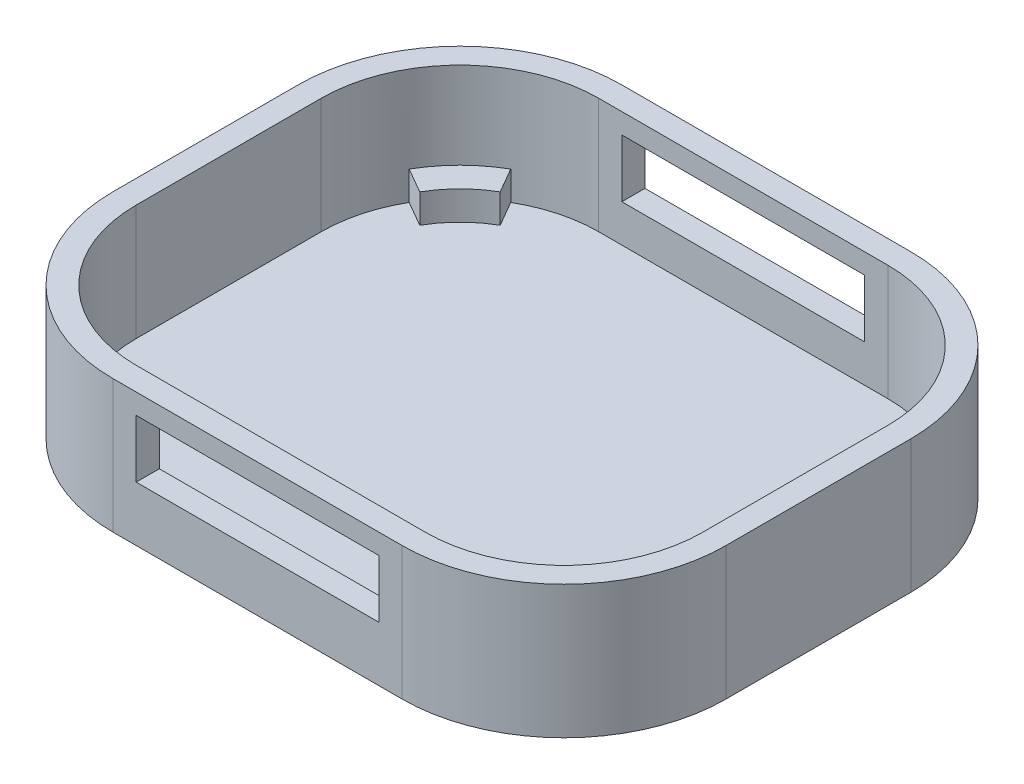
SolidWorks part; units mm, degrees
ref_plane "Front Plane" through (0, 0, 0) normal (0, 0, 1) x (1, 0, 0)
ref_plane "Top Plane" through (0, 0, 0) normal (0, 1, 0) x (1, 0, 0)
ref_plane "Right Plane" through (0, 0, 0) normal (1, 0, 0) x (0, 0, -1)
sketch "Sketch1" plane through (0, 0, 0) normal (0, 1, 0) x (1, 0, 0)
  line L0 (12.5, 22) -> (-12.5, 22) construction
  line L1 (12.5, -20) -> (-12.5, -20)
  line L2 (24.5, -8) -> (24.5, 8)
  line L3 (12.5, 20) -> (-12.5, 20)
  line L4 (-24.5, -8) -> (-24.5, 8)
  line L5 (24.5, -20) -> (-24.5, 20) construction
  line L6 (24.5, 20) -> (-24.5, -20) construction
  line L7 (26.5, -8) -> (26.5, 8) construction
  line L8 (12.5, -22) -> (-12.5, -22) construction
  line L9 (-26.5, -8) -> (-26.5, 8) construction
  line L10 (-26.5, 8) -> (-26.5, -8)
  line L11 (-12.5, -22) -> (12.5, -22)
  line L12 (26.5, -8) -> (26.5, 8)
  line L13 (12.5, 22) -> (-12.5, 22)
  arc A0 (12.5, 20) -> (24.5, 8) centre (12.5, 8) cw
  arc A1 (24.5, -8) -> (12.5, -20) centre (12.5, -8) cw
  arc A2 (-12.5, -20) -> (-24.5, -8) centre (-12.5, -8) cw
  arc A3 (-24.5, 8) -> (-12.5, 20) centre (-12.5, 8) cw
  arc A4 (-26.5, 8) -> (-12.5, 22) centre (-12.5, 8) cw construction
  arc A5 (12.5, 22) -> (26.5, 8) centre (12.5, 8) cw construction
  arc A6 (26.5, -8) -> (12.5, -22) centre (12.5, -8) cw construction
  arc A7 (-12.5, -22) -> (-26.5, -8) centre (-12.5, -8) cw construction
  arc A8 (-12.5, 22) -> (-26.5, 8) centre (-12.5, 8) ccw
  arc A9 (-26.5, -8) -> (-12.5, -22) centre (-12.5, -8) ccw
  arc A10 (12.5, -22) -> (26.5, -8) centre (12.5, -8) ccw
  arc A11 (26.5, 8) -> (12.5, 22) centre (12.5, 8) ccw
  point P0 (0, 0)
  point P33 (26.5, 0)
  point P43 (-26.5, 0)
  point P44 (0, 22)
  dimension "D3" = 12
  dimension "D1" = 53
  dimension "D2" = 44
  dimension "D5" = 16
  dimension "D4" = 2
extrude "Boss-Extrude1" add sketch "Sketch1" along normal mid plane 11.5
sketch "Sketch2" plane through (0, 0, -20) normal (0, 0, 1) x (1, 0, 0)
  line L0 (-26.5, 0) -> (26.5, 0) construction
  line L1 (-10.5, 4) -> (10.5, 4)
  line L2 (-10.5, 4) -> (-10.5, -1)
  line L3 (-10.5, -1) -> (10.5, -1)
  line L4 (10.5, 4) -> (10.5, -1)
  line L5 (-10.5, 4) -> (10.5, -1) construction
  line L6 (-10.5, -1) -> (10.5, 4) construction
  line L9 (-26.5, 5.75) -> (-26.5, -5.75) construction
  line L10 (26.5, 5.75) -> (26.5, -5.75) construction
  line L11 (0, 5.75) -> (0, -5.75) construction
  line L12 (-12.5, 5.75) -> (12.5, 5.75) construction
  line L13 (-12.5, -5.75) -> (12.5, -5.75) construction
  point P0 (0, 1.5)
  dimension "D1" = 21
  dimension "D2" = 5
  dimension "D3" = 1.75
extrude "Cut-Extrude1" cut sketch "Sketch2" against normal through all both and the other way through all
sketch "Sketch3" plane through (0, -5.75, 0) normal (0, -1, 0) x (1, 0, 0)
  line L4 (-12.5, -22) -> (12.5, -22)
  line L5 (26.5, -8) -> (26.5, 8)
  line L12 (12.5, 22) -> (-12.5, 22)
  line L13 (-26.5, 8) -> (-26.5, -8)
  line L14 (-12.5, -22) -> (12.5, -22)
  line L15 (26.5, -8) -> (26.5, 8)
  line L16 (12.5, 22) -> (-12.5, 22)
  line L17 (-26.5, 8) -> (-26.5, -8)
  arc A12 (-26.5, -8) -> (-12.5, -22) centre (-12.5, -8) ccw
  arc A13 (12.5, -22) -> (26.5, -8) centre (12.5, -8) ccw
  arc A14 (26.5, 8) -> (12.5, 22) centre (12.5, 8) ccw
  arc A15 (-12.5, 22) -> (-26.5, 8) centre (-12.5, 8) ccw
  arc A16 (-26.5, -8) -> (-12.5, -22) centre (-12.5, -8) ccw
  arc A17 (12.5, -22) -> (26.5, -8) centre (12.5, -8) ccw
  arc A18 (26.5, 8) -> (12.5, 22) centre (12.5, 8) ccw
  arc A19 (-12.5, 22) -> (-26.5, 8) centre (-12.5, 8) ccw
  dimension "D1" = 0
extrude "Boss-Extrude2" add sketch "Sketch3" against normal blind 1.5
sketch "Sketch4" plane through (0, 0, -22) normal (0, 0, -1) x (-1, 0, 0)
  line L5 (-10.5, -5) -> (10.5, -5)
  line L6 (-10.5, -5) -> (-10.5, -10)
  line L7 (-10.5, -10) -> (10.5, -10)
  line L9 (10.5, -5) -> (10.5, -10)
  line L10 (-10.5, -5) -> (10.5, -10) construction
  line L11 (-10.5, -10) -> (10.5, -5) construction
  point P0 (0, -7.5)
  dimension "D1" = 5
  dimension "D2" = 21
  dimension "D3" = 7.5
extrude "Cut-Extrude2" [suppressed] cut sketch "Sketch4" against normal blind 2
sketch "Sketch5" plane through (0, -4.25, 0) normal (0, 1, 0) x (-1, 0, 0)
  line L0 (-24.3987, 0) -> (22.5042, 0) construction
  line L5 (-11, 19) -> (11, 12) construction
  line L6 (-11, 12) -> (11, 19) construction
  line L7 (-11, -12) -> (11, -12)
  line L8 (11, -19) -> (11, -12)
  line L9 (-11, -19) -> (11, -19)
  line L10 (-11, -19) -> (-11, -12)
  point P0 (0, 15.5)
  dimension "D1" = 7
  dimension "D2" = 22
  dimension "D3" = 15.5
extrude "Cut-Extrude3" [suppressed] cut sketch "Sketch5" against normal blind 2
sketch "Sketch6" plane through (0, -4.25, 0) normal (0, 1, 0) x (1, 0, 0)
  line L0 (0, -20) -> (0, 20) construction
  line L1 (-24.5, 0) -> (24.5, 0) construction
  line L2 (-22.8923, 14) -> (-20.7272, 12.75)
  line L3 (-17.25, 16.2272) -> (-18.5, 18.3923)
  line L4 (-19.2175, 14.7175) -> (-20.9853, 16.4853) construction
  line L5 (-20.7272, 12.75) -> (-12.5, 8) construction
  line L6 (-12.5, 8) -> (-19.2175, 14.7175) construction
  line L7 (-12.5, 8) -> (-17.25, 16.2272) construction
  line L8 (17.25, 16.2272) -> (18.5, 18.3923)
  line L9 (22.8923, 14) -> (20.7272, 12.75)
  line L10 (22.8923, -14) -> (20.7272, -12.75)
  line L11 (17.25, -16.2272) -> (18.5, -18.3923)
  line L12 (-17.25, -16.2272) -> (-18.5, -18.3923)
  line L13 (-22.8923, -14) -> (-20.7272, -12.75)
  line L14 (-24.5, -8) -> (-24.5, 8) construction
  line L15 (12.5, 20) -> (-12.5, 20) construction
  line L16 (12.5, -20) -> (-12.5, -20) construction
  line L17 (24.5, -8) -> (24.5, 8) construction
  arc A0 (-22.8923, 14) -> (-18.5, 18.3923) centre (-12.5, 8) cw
  arc A1 (-20.7272, 12.75) -> (-17.25, 16.2272) centre (-12.5, 8) cw
  arc A2 (22.8923, 14) -> (18.5, 18.3923) centre (12.5, 8) ccw
  arc A3 (20.7272, 12.75) -> (17.25, 16.2272) centre (12.5, 8) ccw
  arc A4 (20.7272, -12.75) -> (17.25, -16.2272) centre (12.5, -8) cw
  arc A5 (22.8923, -14) -> (18.5, -18.3923) centre (12.5, -8) cw
  arc A6 (-22.8923, -14) -> (-18.5, -18.3923) centre (-12.5, -8) ccw
  arc A7 (-20.7272, -12.75) -> (-17.25, -16.2272) centre (-12.5, -8) ccw
  arc A8 (-12.5, 20) -> (-24.5, 8) centre (-12.5, 8) ccw construction
  dimension "D3" = 2.5
  dimension "D1" = 45
  dimension "D2" = 30
extrude "Boss-Extrude3" add sketch "Sketch6" along normal blind 2.5
